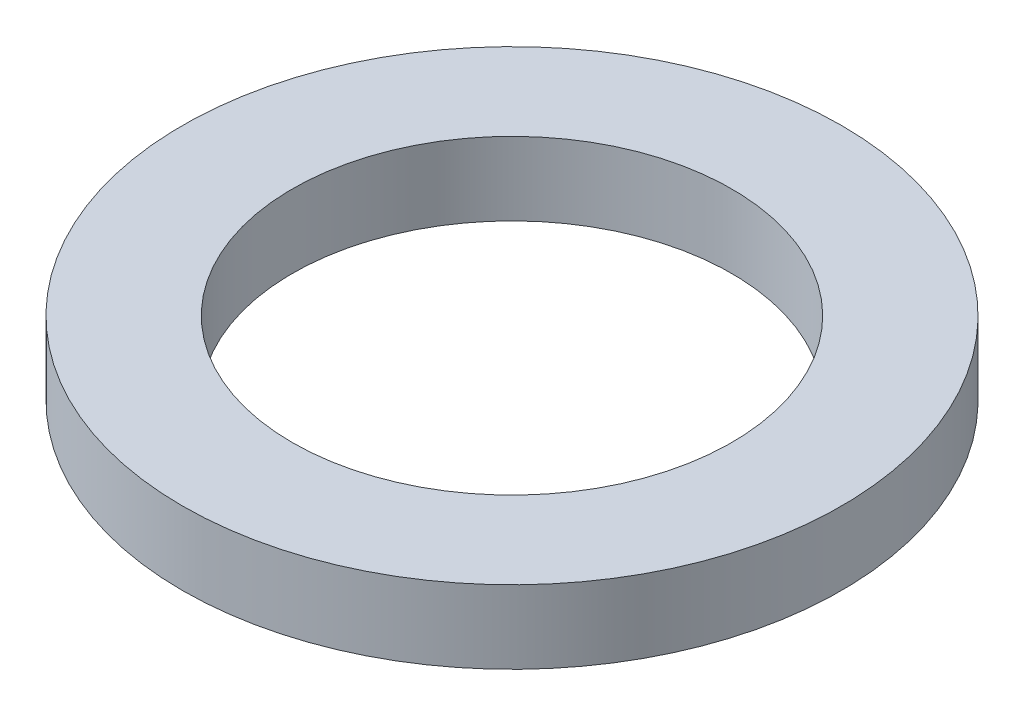
SolidWorks part; units mm, degrees
ref_plane "Front Plane" through (0, 0, 0) normal (0, 0, 1) x (1, 0, 0)
ref_plane "Top Plane" through (0, 0, 0) normal (0, 1, 0) x (1, 0, 0)
ref_plane "Right Plane" through (0, 0, 0) normal (1, 0, 0) x (0, 0, -1)
sketch "Sketch1" plane through (0, 0, 0) normal (0, 1, 0) x (1, 0, 0)
  circle A0 centre (0, 0) radius 15
  circle A1 centre (0, 0) radius 22.5
  dimension "D1" = 30
  dimension "D2" = 45
extrude "Boss-Extrude1" add sketch "Sketch1" along normal blind 5
